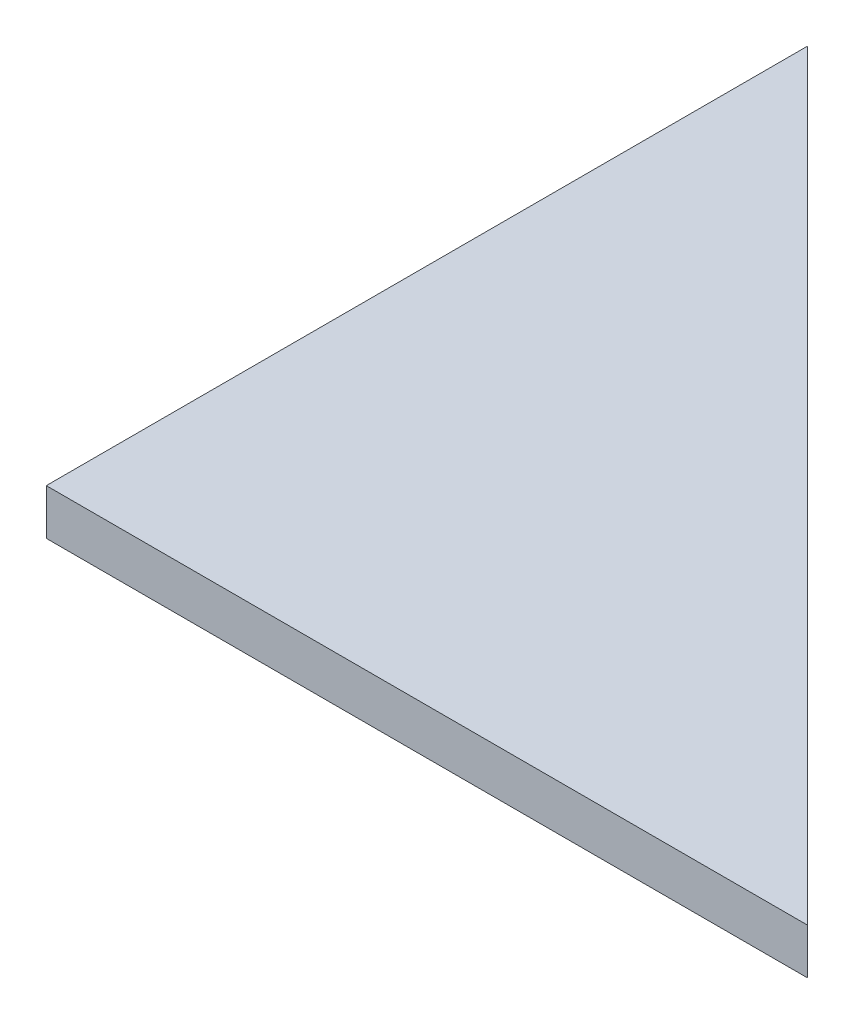
SolidWorks part; units mm, degrees
ref_plane "Přední rovina" through (0, 0, 0) normal (0, 0, 1) x (1, 0, 0)
ref_plane "Horní rovina" through (0, 0, 0) normal (0, 1, 0) x (1, 0, 0)
ref_plane "Pravá rovina" through (0, 0, 0) normal (1, 0, 0) x (0, 0, -1)
sketch "Skica1" plane through (0, 0, 0) normal (0, 1, 0) x (1, 0, 0)
  line L0 (0, 50) -> (50, 0)
  line L1 (0, 0) -> (50, 0)
  line L2 (0, 0) -> (0, 50)
  line L3 (0, 50) -> (50, 50)
  line L4 (50, 0) -> (50, 50)
  dimension "D1" = 50
  dimension "D2" = 50
extrude "Přidat vysunutím1" add sketch "Skica1" along normal blind 3 contours L2 L1 L0
